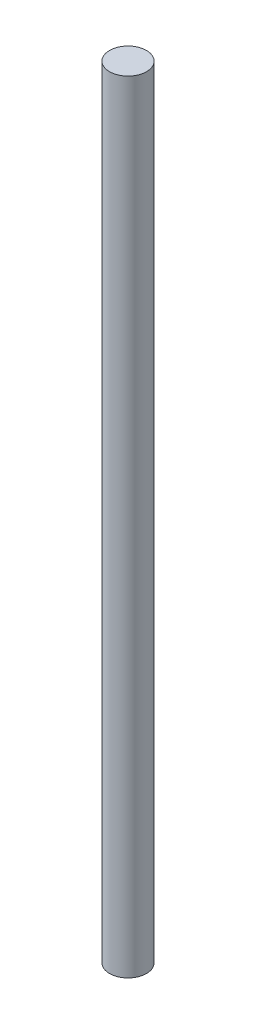
SolidWorks part; units mm, degrees
material "Ductile Iron (SN)"
ref_plane "Front Plane" through (0, 0, 0) normal (0, 0, 1) x (1, 0, 0)
ref_plane "Top Plane" through (0, 0, 0) normal (0, 1, 0) x (1, 0, 0)
ref_plane "Right Plane" through (0, 0, 0) normal (1, 0, 0) x (0, 0, -1)
sketch "Sketch2" plane through (0, 0, 0) normal (0, 1, 0) x (1, 0, 0)
  circle A0 centre (0, 0) radius 15
  dimension "D1" = 30
extrude "Boss-Extrude1" add sketch "Sketch2" along normal blind 635
